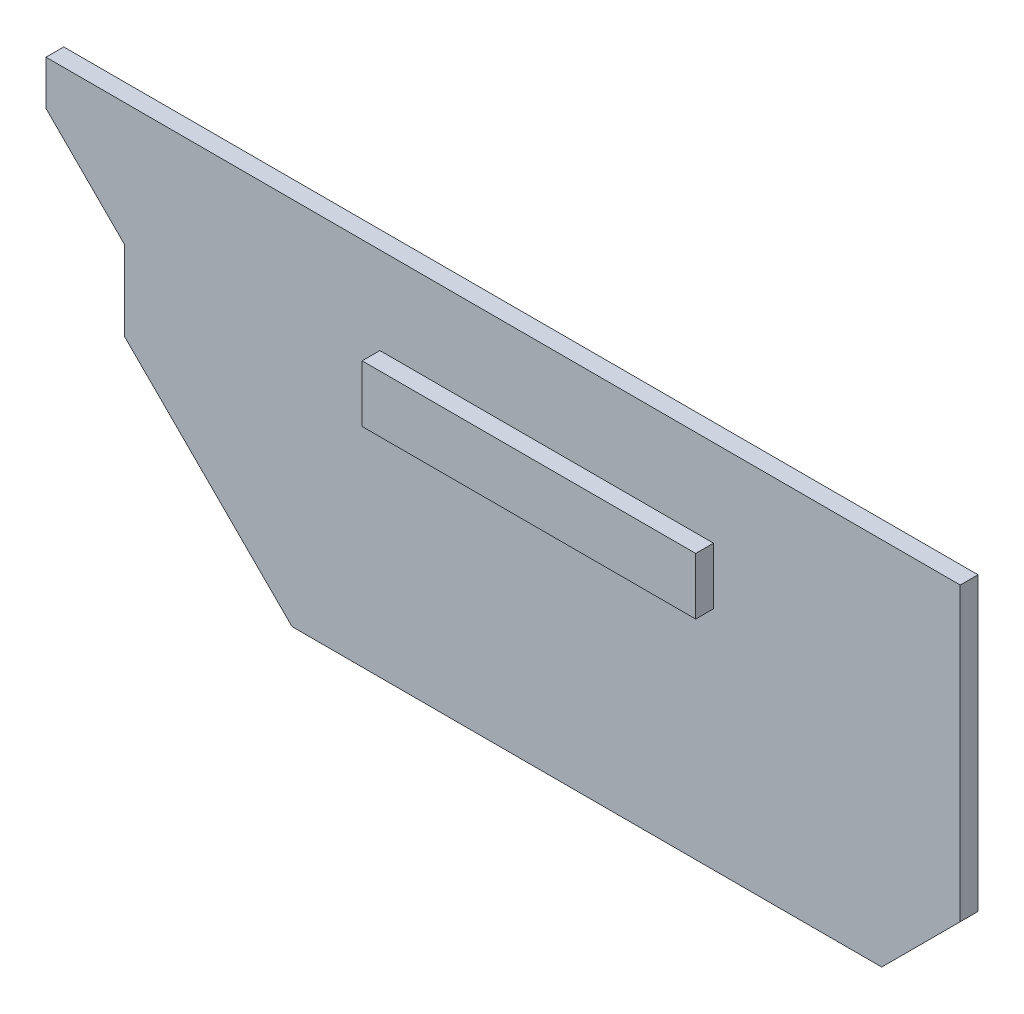
SolidWorks part; units mm, degrees
material "1060 Alloy"
ref_plane "Front Plane" through (0, 0, 0) normal (0, 0, 1) x (1, 0, 0)
ref_plane "Top Plane" through (0, 0, 0) normal (0, 1, 0) x (1, 0, 0)
ref_plane "Right Plane" through (0, 0, 0) normal (1, 0, 0) x (0, 0, -1)
sketch "Sketch1" plane through (0, 0, 0) normal (0, 0, 1) x (1, 0, 0)
  line L0 (0, 0) -> (123.5, 0)
  line L1 (123.5, 0) -> (123.5, -39.3934)
  line L2 (123.5, -39.3934) -> (112.8934, -50)
  line L3 (112.8934, -50) -> (33.234, -50)
  line L4 (33.234, -50) -> (10.6066, -27.3726)
  line L5 (10.6066, -27.3726) -> (10.6066, -16.6066)
  line L6 (10.6066, -16.6066) -> (0, -6)
  line L7 (0, -6) -> (0, 0)
  dimension "D1" = 123.5
  dimension "D2" = 50
  dimension "D3" = 15
  dimension "D4" = 6
  dimension "D5" = 15
  dimension "D6" = 32
  dimension "D7" = 135
  dimension "D8" = 135
  dimension "D9" = 135
extrude "Boss-Extrude1" add sketch "Sketch1" along normal blind 2.4
sketch "Sketch2" plane through (0, 0, 2.4) normal (0, 0, 1) x (1, 0, 0)
  line L0 (123.5, 0) -> (0, 0) construction
  line L1 (45.1066, -11.77) -> (90.1666, -11.77)
  line L2 (45.1066, -11.77) -> (45.1066, -19.45)
  line L3 (45.1066, -19.45) -> (90.1666, -19.45)
  line L4 (90.1666, -11.77) -> (90.1666, -19.45)
  line L5 (10.6066, -16.6066) -> (10.6066, -27.3726) construction
  dimension "D1" = 7.68
  dimension "D2" = 45.06
  dimension "D3" = 11.77
  dimension "D4" = 34.5
extrude "Boss-Extrude2" add sketch "Sketch2" along normal blind 2.4
